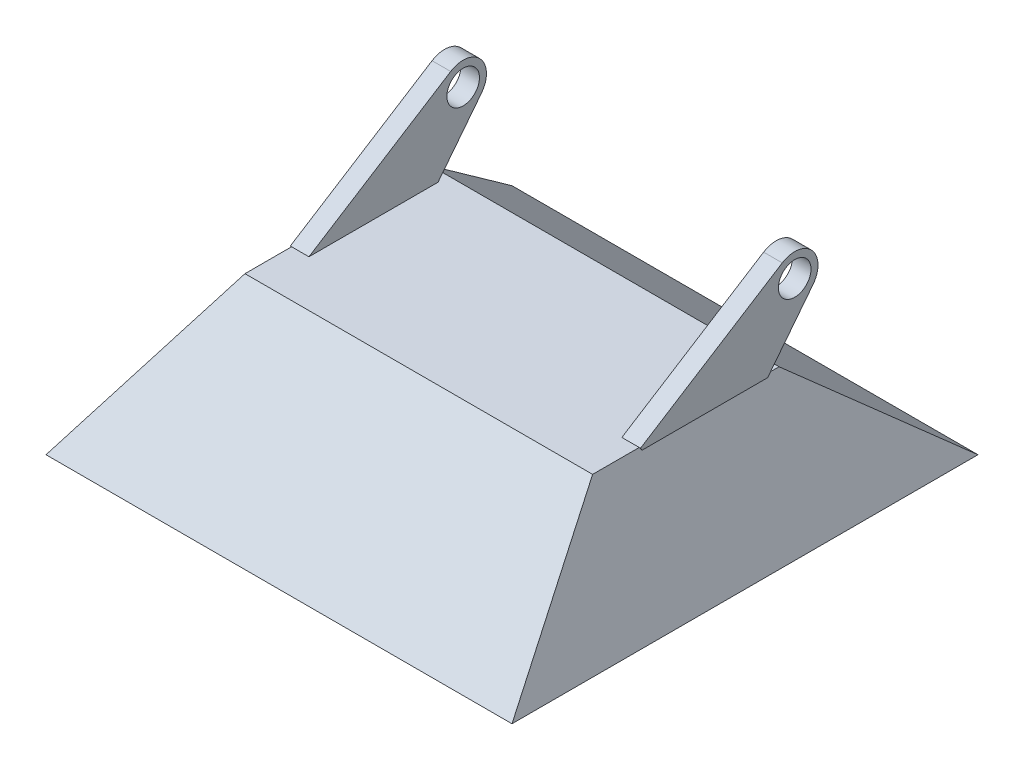
SolidWorks part; units mm, degrees
ref_plane "Front" through (0, 0, 0) normal (0, 0, 1) x (1, 0, 0)
ref_plane "Top" through (0, 0, 0) normal (0, 1, 0) x (1, 0, 0)
ref_plane "Right" through (0, 0, 0) normal (1, 0, 0) x (0, 0, -1)
ref_plane "Plane1" through (0, 125, 0) normal (0, 1, 0) x (1, 0, 0)
sketch "Sketch2" plane through (0, 0, 0) normal (0, 1, 0) x (1, 0, 0)
  line L1 (250, -250) -> (-250, -250)
  line L2 (250, -250) -> (250, 250)
  line L3 (250, 250) -> (-250, 250)
  line L4 (-250, -250) -> (-250, 250)
  line L5 (250, -250) -> (-250, 250) construction
  line L6 (250, 250) -> (-250, -250) construction
  point P0 (0, 0)
  dimension "D1" = 500
  dimension "D2" = 500
sketch "Sketch3" plane through (0, 125, 0) normal (0, 1, 0) x (1, 0, 0)
  line L1 (186.5, -100) -> (-186.5, -100)
  line L2 (186.5, -100) -> (186.5, 100)
  line L3 (186.5, 100) -> (-186.5, 100)
  line L4 (-186.5, -100) -> (-186.5, 100)
  line L5 (186.5, -100) -> (-186.5, 100) construction
  line L6 (186.5, 100) -> (-186.5, -100) construction
  point P0 (0, 0)
  dimension "D1" = 200
  dimension "D2" = 373
loft "Loft1" add profiles "Sketch3", "Sketch2"
sketch "Sketch4" plane through (0, 0, 0) normal (0, -1, 0) x (1, 0, 0)
  circle A0 centre (0, 0) radius 137.5
  dimension "D1" = 275
extrude "Cut-Extrude1" cut sketch "Sketch4" against normal blind 20
sketch "Sketch5" plane through (0, 54.7828, 0) normal (1, 0, 0) x (0, 0, -1)
  line L0 (0, -54.7828) -> (115.4701, 145.2172) construction
  line L1 (18.7491, -54.7828) -> (76.488, -54.7828) construction
  line L2 (102.1141, 166.3506) -> (-50, 70.2172)
  line L3 (-100, 70.2172) -> (100, 70.2172) construction
  line L4 (135.1549, 129.8059) -> (11.8646, -27.6727)
  line L6 (-50, 70.2172) -> (11.8646, -27.6727)
  arc A0 (135.1549, 129.8059) -> (102.1141, 166.3506) centre (115.4701, 145.2172) ccw
  point P7 (0, 0)
  dimension "D2" = 50
  dimension "D1" = 60
  dimension "D3" = 200
  dimension "D4" = 50
  dimension "D5" = 200
  dimension "D6" = 54.2202
extrude "Boss-Extrude1" add sketch "Sketch5" along normal blind 20 from offset 167.87
sketch "Sketch6" plane through (187.87, 0, 0) normal (1, 0, 0) x (0, 0, -1)
  circle A0 centre (115.4701, 200) radius 17.5
  dimension "D1" = 35
extrude "Cut-Extrude2" cut sketch "Sketch6" against normal through all
mirror "Mirror1" about plane through (0, 0, 0) normal (1, 0, 0) of "Cut-Extrude2", "Boss-Extrude1"
